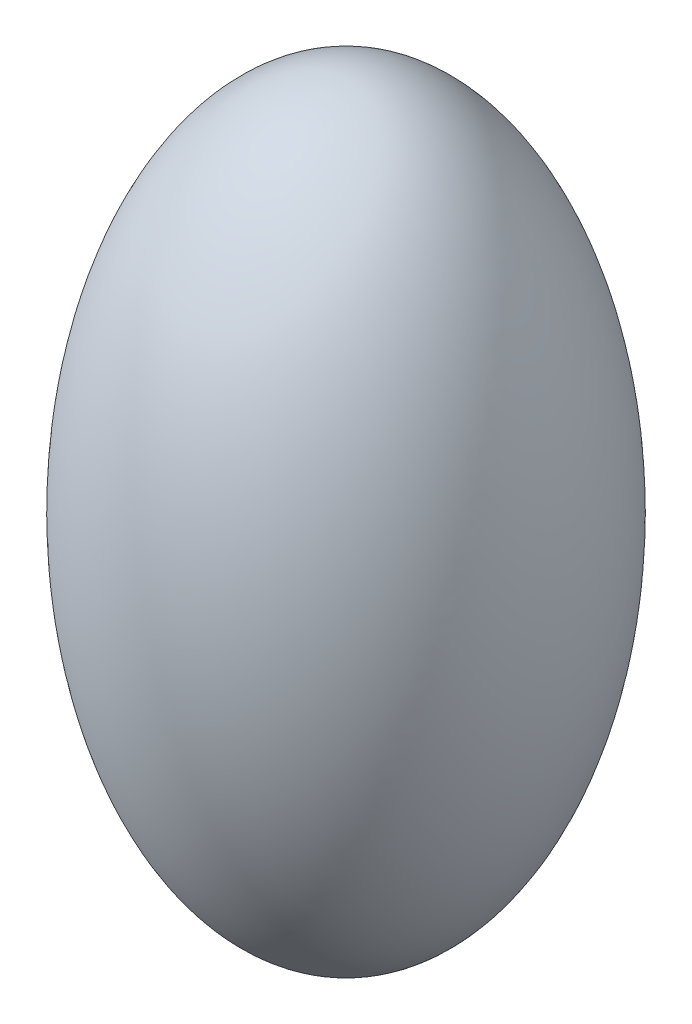
SolidWorks part; units mm, degrees
ref_plane "Plano frontal" through (0, 0, 0) normal (0, 0, 1) x (1, 0, 0)
ref_plane "Plano superior" through (0, 0, 0) normal (0, 1, 0) x (1, 0, 0)
ref_plane "Plano direito" through (0, 0, 0) normal (1, 0, 0) x (0, 0, -1)
sketch "Esboço1" plane through (0, 0, 0) normal (1, 0, 0) x (0, 0, -1)
  line L0 (0, 30.1714) -> (0, -30.1714) construction
  line L1 (0, 30.1714) -> (0, -30.1714)
  ellipse E0 centre (0, 0) end of major axis (0, 30.1714) minor radius 17.0346 (0, -30.1714) -> (0, 30.1714) ccw
revolve "Revolução1" add sketch "Esboço1" angle 360 about L0
